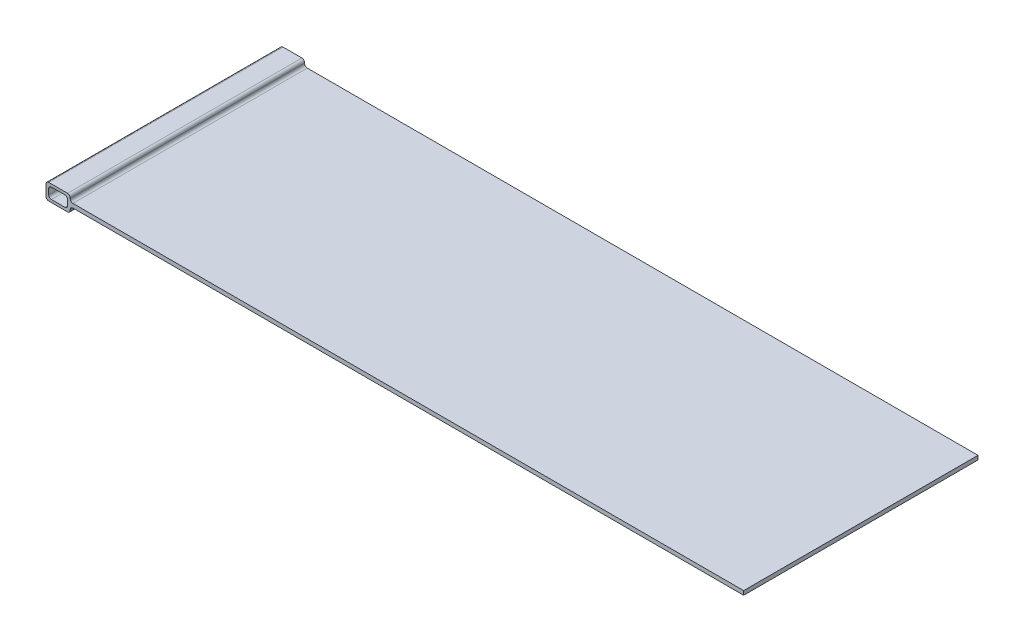
SolidWorks part; units mm, degrees
ref_plane "前视基准面" through (0, 0, 0) normal (0, 0, 1) x (1, 0, 0)
ref_plane "上视基准面" through (0, 0, 0) normal (0, 1, 0) x (1, 0, 0)
ref_plane "右视基准面" through (0, 0, 0) normal (1, 0, 0) x (0, 0, -1)
sketch "草图1" plane through (0, 0, 0) normal (0, 0, 1) x (1, 0, 0)
  line L0 (9, -1.25) -> (9, -1)
  line L1 (1, 0) -> (8, 0)
  line L2 (0, -1) -> (0, -5)
  line L3 (1, -6) -> (8, -6)
  line L5 (10, -2.25) -> (259, -2.25)
  line L7 (10, -3.75) -> (259, -3.75)
  line L8 (259, -2.25) -> (259, -3.75)
  line L9 (9, -4.75) -> (9, -5)
  arc A0 (1, 0) -> (0, -1) centre (1, -1) ccw
  arc A1 (0, -5) -> (1, -6) centre (1, -5) ccw
  arc A2 (8, -6) -> (9, -5) centre (8, -5) ccw
  arc A3 (8, 0) -> (9, -1) centre (8, -1) cw
  arc A4 (9, -4.75) -> (10, -3.75) centre (10, -4.75) cw
  arc A5 (10, -2.25) -> (9, -1.25) centre (10, -1.25) cw
  point P11 (0, 0)
  point P15 (0, -6)
  point P20 (9, 0)
  point P23 (9, -3.75)
  point P26 (9, -2.25)
  dimension "D1" = 6
  dimension "D5" = 1
  dimension "D6" = 1
  dimension "D2" = 1.5
  dimension "D3" = 9
  dimension "D4" = 250
extrude "凸台-拉伸1" add sketch "草图1" along normal blind 87
sketch "草图2" plane through (0, 0, 87) normal (0, 0, 1) x (1, 0, 0)
  line L0 (8, 0) -> (1, 0) construction
  line L1 (2, -1) -> (7, -1)
  line L2 (1, -2) -> (1, -4)
  line L3 (2, -5) -> (7, -5)
  line L4 (8, -2) -> (8, -4)
  line L5 (1, -6) -> (8, -6) construction
  line L6 (0, -1) -> (0, -5) construction
  line L7 (9, -1.25) -> (9, -1) construction
  arc A0 (7, -1) -> (8, -2) centre (7, -2) cw
  arc A1 (7, -5) -> (8, -4) centre (7, -4) ccw
  arc A2 (1, -4) -> (2, -5) centre (2, -4) ccw
  arc A3 (2, -1) -> (1, -2) centre (2, -2) ccw
  dimension "D5" = 1
  dimension "D1" = 1
  dimension "D2" = 1
  dimension "D3" = 1
  dimension "D4" = 1
extrude "切除-拉伸1" cut sketch "草图2" against normal through all
